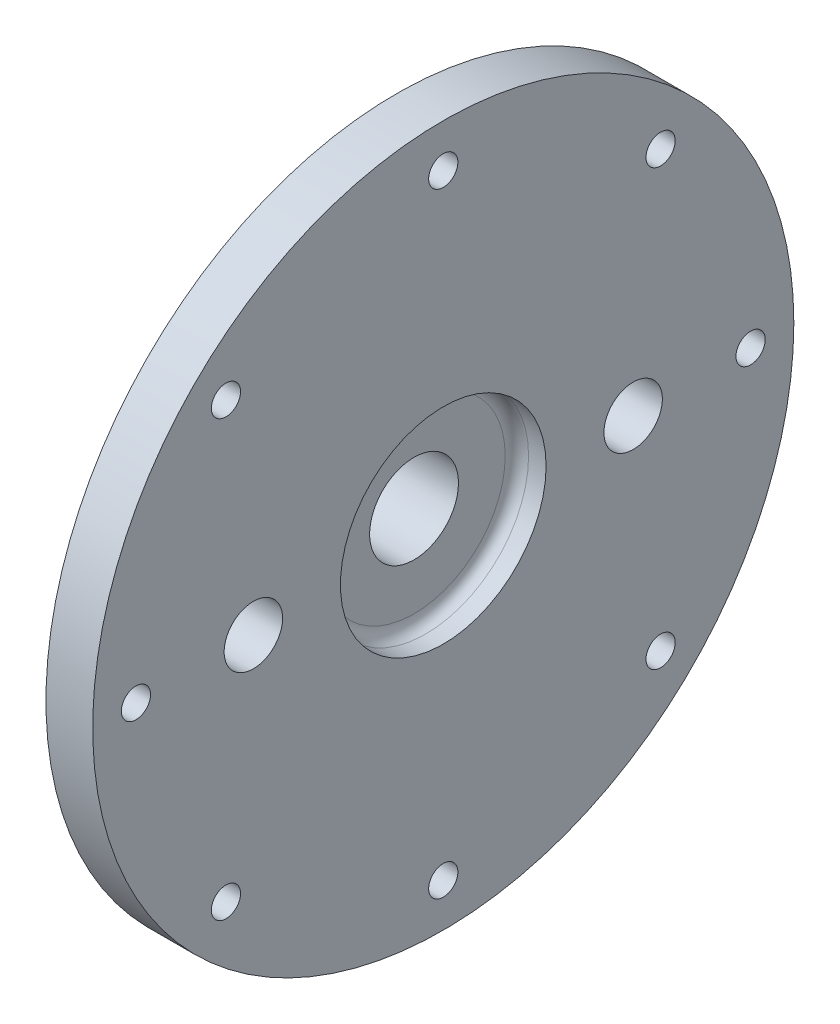
SolidWorks part; units mm, degrees
ref_plane "Front Plane" through (0, 0, 0) normal (0, 0, 1) x (1, 0, 0)
ref_plane "Top Plane" through (0, 0, 0) normal (0, 1, 0) x (1, 0, 0)
ref_plane "Right Plane" through (0, 0, 0) normal (1, 0, 0) x (0, 0, -1)
sketch "Sketch1" plane through (0, 0, 0) normal (0, 0, 1) x (1, 0, 0)
  line L1 (0, 76.2) -> (-10.16, 76.2)
  line L2 (-10.16, 76.2) -> (-10.16, 21.082)
  line L3 (-15.24, 16.002) -> (-31.75, 16.002)
  line L4 (-31.75, 16.002) -> (-31.75, 9.652)
  line L5 (-31.75, 9.652) -> (-6.35, 9.652)
  line L6 (-6.35, 9.652) -> (-6.35, 19.812)
  line L7 (-3.81, 22.352) -> (0, 22.352)
  line L8 (0, 22.352) -> (0, 76.2)
  line L9 (0, 0) -> (-31.75, 0) construction
  line L10 (-31.75, 0) -> (-31.75, 9.652) construction
  arc A0 (-10.16, 21.082) -> (-15.24, 16.002) centre (-15.24, 21.082) cw
  arc A2 (-6.35, 19.812) -> (-3.81, 22.352) centre (-3.81, 19.812) cw
  dimension "D1" = 5.08
  dimension "D4" = 2.54
  dimension "D2" = 6.35
  dimension "D3" = 12.7
  dimension "D5" = 3.81
  dimension "D6" = 9.652
  dimension "D7" = 6.35
  dimension "D8" = 25.4
  dimension "D9" = 76.2
revolve "Revolve1" add sketch "Sketch1" angle 360 about L9
sketch "Sketch2" plane through (0, 0, 0) normal (1, 0, 0) x (0, 0, -1)
  line L0 (-41.275, 0) -> (41.275, 0) construction
  circle A0 centre (41.275, 0) radius 6.35
  circle A1 centre (-41.275, 0) radius 6.35
  point P8 (0, 0)
  dimension "D1" = 12.7
  dimension "D2" = 82.55
extrude "Cut-Extrude1" cut sketch "Sketch2" against normal through all and the other way through all
sketch "Sketch3" plane through (0, 0, 0) normal (1, 0, 0) x (0, 0, -1)
  line L0 (0, 0) -> (66.802, 0) construction
  circle A0 centre (66.802, 0) radius 3.175
  dimension "D1" = 6.35
  dimension "D2" = 66.802
extrude "Cut-Extrude2" cut sketch "Sketch3" against normal through all
pattern_circular "CirPattern1" count 8 over 360 about axis through (0, 0, 0) along (1, 0, 0) of "Cut-Extrude2"
